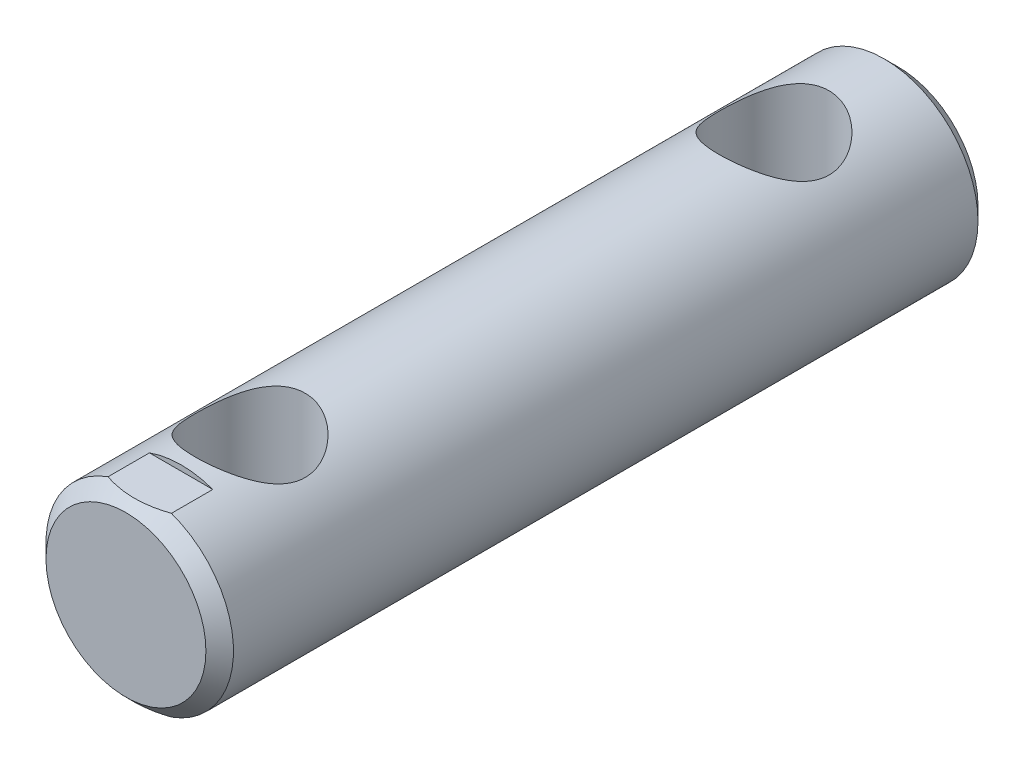
SolidWorks part; units mm, degrees
material "Acier non allié"
ref_plane "Plan de face" through (0, 0, 0) normal (0, 0, 1) x (1, 0, 0)
ref_plane "Plan de dessus" through (0, 0, 0) normal (0, 1, 0) x (1, 0, 0)
ref_plane "Plan de droite" through (0, 0, 0) normal (1, 0, 0) x (0, 0, -1)
sketch "Esquisse1" plane through (0, 0, 0) normal (0, 0, 1) x (1, 0, 0)
  circle A0 centre (0, 0) radius 3.4
  dimension "D1" = 6.8
extrude "Boss.-Extru.1" add sketch "Esquisse1" along normal blind 28
sketch "Esquisse2" plane through (0, 0, 0) normal (0, 1, 0) x (1, 0, 0)
  line L0 (0, 0) -> (0, -28) construction
  line L1 (3.4, 0) -> (-3.4, 0) construction
  line L2 (-3.4, -28) -> (3.4, -28) construction
  circle A0 centre (0, -4.5) radius 2
  circle A1 centre (0, -23.5) radius 2
  dimension "D1" = 4
  dimension "D2" = 19
  dimension "D3" = 4.5
  dimension "D4" = 4.5
extrude "Enlèv. mat.-Extru.1" cut sketch "Esquisse2" against normal through all and the other way through all
chamfer "Chanfrein1" distance 0.5 angle 45 2 edges at (3.4, 0, 28) (3.4, 0, 0)
sketch "Esquisse3" plane through (0, 0, 28) normal (0, 0, 1) x (1, 0, 0)
  line L0 (0, 0) -> (0, 3.2) construction
  line L1 (-3.1298, 5.5307) -> (3.1298, 5.5307)
  line L2 (-3.1298, 5.5307) -> (-3.1298, 3.2)
  line L3 (-3.1298, 3.2) -> (3.1298, 3.2)
  line L4 (3.1298, 5.5307) -> (3.1298, 3.2)
  line L5 (-3.1298, -5.5307) -> (3.1298, -5.5307)
  line L6 (-3.1298, -5.5307) -> (-3.1298, -3.2)
  line L7 (-3.1298, -3.2) -> (3.1298, -3.2)
  line L8 (3.1298, -5.5307) -> (3.1298, -3.2)
  line L9 (0, 0) -> (0, -3.2) construction
  dimension "D1" = 3.2
  dimension "D2" = 2.3307
  dimension "D3" = 6.2596
extrude "Enlèv. mat.-Extru.2" cut sketch "Esquisse3" against normal blind 2
